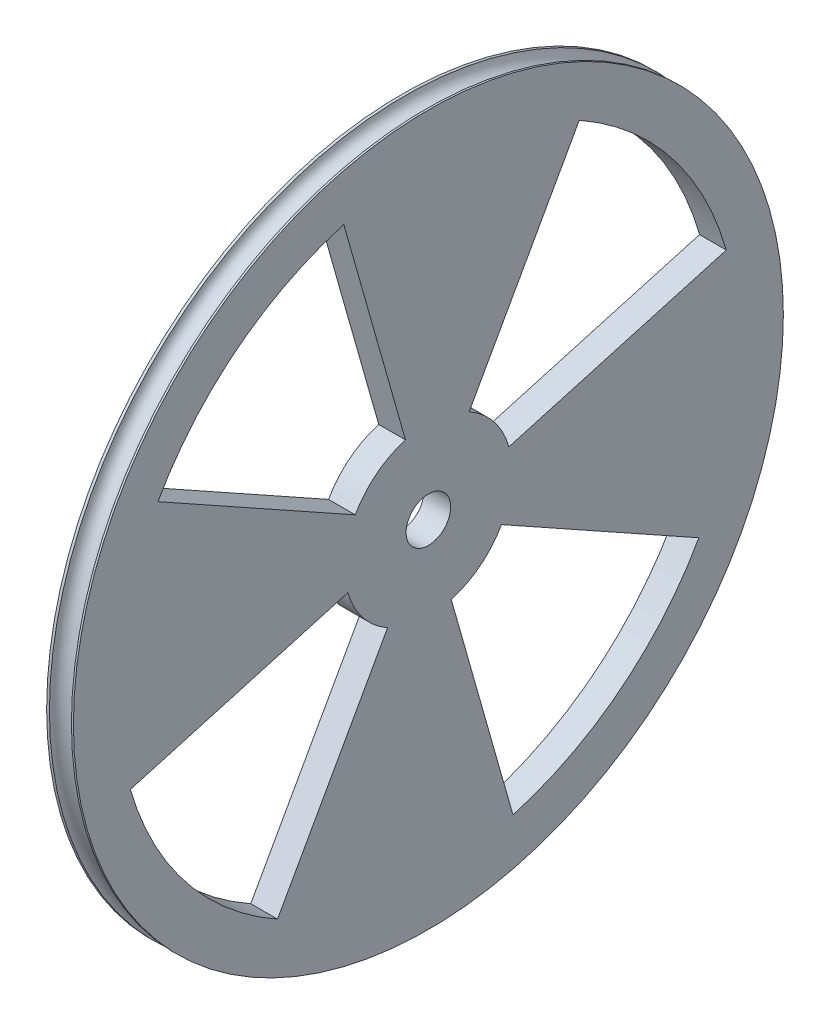
SolidWorks part; units mm, degrees
ref_plane "Front Plane" through (0, 0, 0) normal (0, 0, 1) x (1, 0, 0)
ref_plane "Top Plane" through (0, 0, 0) normal (0, 1, 0) x (1, 0, 0)
ref_plane "Right Plane" through (0, 0, 0) normal (1, 0, 0) x (0, 0, -1)
sketch "Sketch1" plane through (0, 0, 0) normal (0, 0, 1) x (1, 0, 0)
  line L0 (0, 0) -> (3.81, 0)
  line L3 (0.3963, 50.546) -> (0, 50.546)
  line L4 (0, 50.546) -> (0, 0)
  line L5 (3.81, 0) -> (3.81, 50.546)
  line L6 (3.81, 50.546) -> (3.5304, 50.546)
  arc A0 (0.3963, 50.546) -> (3.5304, 50.546) centre (1.9633, 50.8) ccw
  point P3 (0, 0)
  point P8 (0.7935, 49.7269)
  dimension "D1" = 50.8
  dimension "D2" = 1.5875
  dimension "D3" = 3.81
  dimension "D4" = 0.254
revolve "Revolve1" add sketch "Sketch1" angle 360 about L0
sketch "Sketch2" plane through (3.81, 0, 0) normal (1, 0, 0) x (0, 0, -1)
  line L0 (0, 0) -> (-38.5116, 21.4797)
  line L1 (0, 0) -> (-12.0433, 42.4203)
  line L2 (0, 0) -> (21.4797, 38.5116)
  line L3 (0, 0) -> (42.4203, 12.0433)
  line L4 (0, 0) -> (38.5116, -21.4797)
  line L5 (0, 0) -> (12.0433, -42.4203)
  line L6 (0, 0) -> (-21.4797, -38.5116)
  line L7 (0, 0) -> (-42.4203, -12.0433)
  circle A0 centre (0, 0) radius 11.9232
  circle A1 centre (0, 0) radius 3.175
  circle A2 centre (0, 0) radius 44.0967
  point P16 (0, 0)
  dimension "D1" = 6.35
  dimension "D2" = 8
extrude "Cut-Extrude1" cut sketch "Sketch2" against normal through all contours L1 A2 L0 A0 | L3 A2 L2 A0 | L5 A2 L4 A0 | L7 A2 L6 A0 | A1
